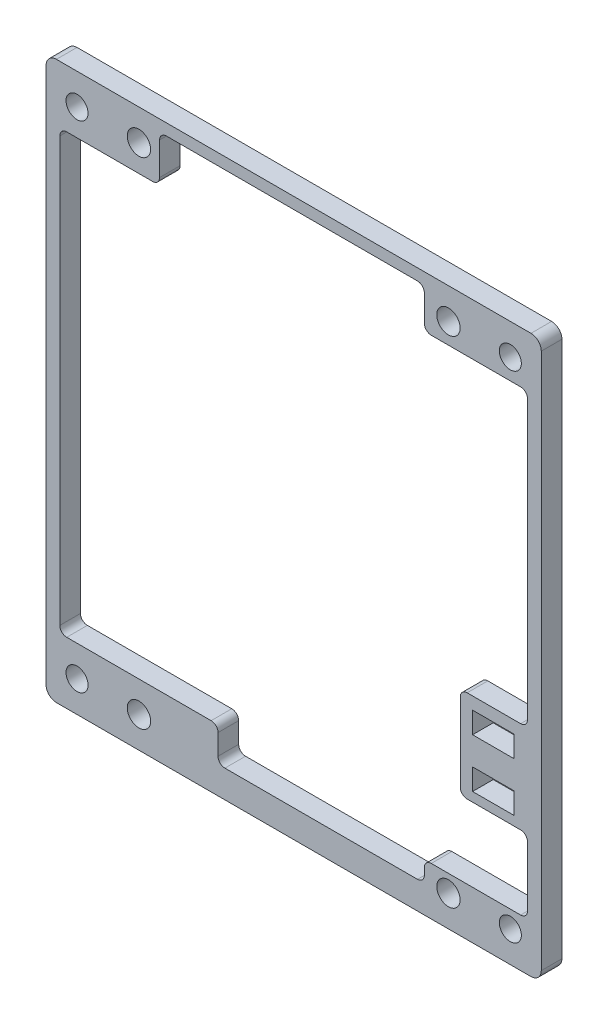
SolidWorks part; units mm, degrees
ref_plane "Alzado" through (0, 0, 0) normal (0, 0, 1) x (1, 0, 0)
ref_plane "Planta" through (0, 0, 0) normal (0, 1, 0) x (1, 0, 0)
ref_plane "Vista lateral" through (0, 0, 0) normal (1, 0, 0) x (0, 0, -1)
sketch "Model" plane through (0, 0, 0) normal (0, 0, 1) x (1, 0, 0)
  line L0 (76.485, 291.7479) -> (76.485, 251.3388)
  line L1 (8.4826, 290.8579) -> (8.4826, 229.2177)
  line L2 (60.485, 298.5848) -> (23.9826, 298.5848)
  line L3 (61.485, 297.5848) -> (61.485, 293.7479)
  line L4 (62.485, 292.7479) -> (75.485, 292.7479)
  line L5 (9.4826, 291.8579) -> (21.9826, 291.8579)
  line L6 (22.9826, 292.8579) -> (22.9826, 297.5848)
  line L7 (31.4826, 224.2411) -> (31.4826, 227.2177)
  line L8 (30.4826, 228.2177) -> (9.4826, 228.2177)
  line L9 (75.485, 226.2433) -> (62.485, 226.2433)
  line L10 (61.485, 224.2411) -> (61.485, 225.2433)
  line L11 (68.4949, 248.5494) -> (68.4949, 245.4494)
  line L12 (68.4949, 248.5494) -> (74.4949, 248.5494)
  line L13 (74.4949, 238.3041) -> (68.4949, 238.3041)
  line L14 (74.4949, 245.4494) -> (68.4949, 245.4494)
  line L15 (74.4949, 248.5494) -> (74.4949, 245.4494)
  line L16 (74.4949, 241.4041) -> (74.4949, 238.3041)
  line L17 (68.4949, 241.4041) -> (74.4949, 241.4041)
  line L18 (68.4949, 238.3041) -> (68.4949, 241.4041)
  line L19 (67.7054, 236.9577) -> (75.485, 236.9577)
  line L20 (66.7051, 249.3388) -> (66.7054, 237.9577)
  line L21 (67.7051, 250.3388) -> (75.485, 250.3388)
  line L22 (76.485, 235.9577) -> (76.485, 227.2433)
  line L23 (76.9852, 300.2457) -> (7.9828, 300.2457)
  line L24 (78.4852, 220.7411) -> (78.4852, 298.7457)
  line L25 (7.9828, 219.2411) -> (76.9852, 219.2411)
  line L26 (6.4828, 298.7457) -> (6.4828, 220.7411)
  line L27 (32.4826, 223.2411) -> (60.485, 223.2411)
  circle A0 centre (19.9821, 223.7408) radius 1.7
  circle A1 centre (64.9856, 223.7408) radius 1.7
  circle A2 centre (10.9825, 223.7408) radius 1.6003
  circle A3 centre (73.9852, 223.7408) radius 1.6003
  circle A4 centre (19.9821, 295.7457) radius 1.7
  circle A5 centre (64.9856, 295.7457) radius 1.7
  circle A6 centre (73.9852, 295.7457) radius 1.6003
  circle A7 centre (10.9825, 295.7457) radius 1.6003
  arc A8 (23.9826, 298.5848) -> (22.9826, 297.5848) centre (23.9826, 297.5848) ccw
  arc A9 (21.9826, 291.8579) -> (22.9826, 292.8579) centre (21.9826, 292.8579) ccw
  arc A10 (9.4826, 291.8579) -> (8.4826, 290.8579) centre (9.4826, 290.8579) ccw
  arc A11 (31.4826, 227.2177) -> (30.4826, 228.2177) centre (30.4826, 227.2177) ccw
  arc A12 (61.485, 297.5848) -> (60.485, 298.5848) centre (60.485, 297.5848) ccw
  arc A13 (61.485, 293.7479) -> (62.485, 292.7479) centre (62.485, 293.7479) ccw
  arc A14 (76.485, 291.7479) -> (75.485, 292.7479) centre (75.485, 291.7479) ccw
  arc A15 (62.485, 226.2433) -> (61.485, 225.2433) centre (62.485, 225.2433) ccw
  arc A16 (75.485, 226.2433) -> (76.485, 227.2433) centre (75.485, 227.2433) ccw
  arc A17 (8.4826, 229.2177) -> (9.4826, 228.2177) centre (9.4826, 229.2177) ccw
  arc A18 (67.7051, 250.3388) -> (66.7051, 249.3388) centre (67.7051, 249.3388) ccw
  arc A19 (66.7054, 237.9577) -> (67.7054, 236.9577) centre (67.7054, 237.9577) ccw
  arc A20 (76.485, 235.9577) -> (75.485, 236.9577) centre (75.485, 235.9577) ccw
  arc A21 (75.485, 250.3388) -> (76.485, 251.3388) centre (75.485, 251.3388) ccw
  arc A22 (7.9828, 300.2457) -> (6.4828, 298.7457) centre (7.9828, 298.7457) ccw
  arc A23 (6.4828, 220.7411) -> (7.9828, 219.2411) centre (7.9828, 220.7411) ccw
  arc A24 (76.9852, 219.2411) -> (78.4852, 220.7411) centre (76.9852, 220.7411) ccw
  arc A25 (78.4852, 298.7457) -> (76.9852, 300.2457) centre (76.9852, 298.7457) ccw
  arc A26 (31.4826, 224.2411) -> (32.4826, 223.2411) centre (32.4826, 224.2411) ccw
  arc A27 (60.485, 223.2411) -> (61.485, 224.2411) centre (60.485, 224.2411) ccw
extrude "Saliente-Extruir1" add sketch "Model" along normal blind 3
